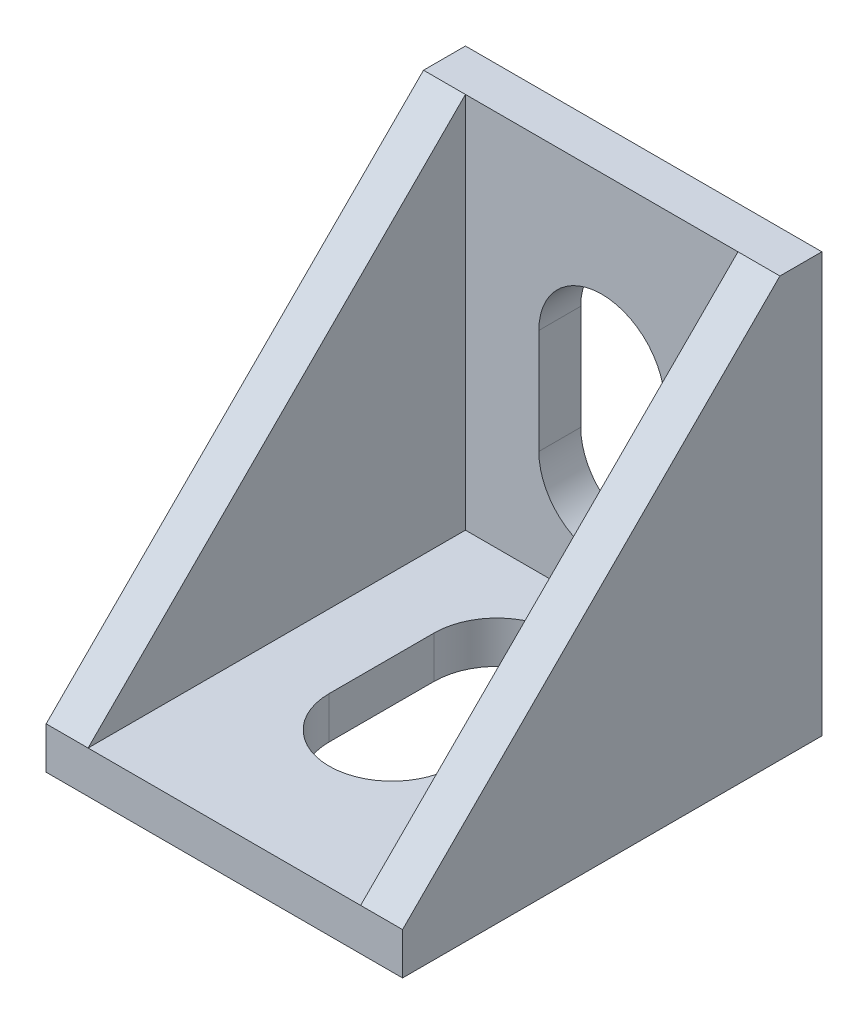
SolidWorks part; units mm, degrees
material "1060 Alloy"
ref_plane "Front Plane" through (0, 0, 0) normal (0, 0, 1) x (1, 0, 0)
ref_plane "Top Plane" through (0, 0, 0) normal (0, 1, 0) x (1, 0, 0)
ref_plane "Right Plane" through (0, 0, 0) normal (1, 0, 0) x (0, 0, -1)
sketch "Sketch1" plane through (0, 0, 0) normal (0, 0, 1) x (1, 0, 0)
  line L1 (-8.5, -10) -> (8.5, -10)
  line L2 (-8.5, -10) -> (-8.5, 10)
  line L3 (-8.5, 10) -> (8.5, 10)
  line L4 (8.5, -10) -> (8.5, 10)
  line L5 (-8.5, -10) -> (8.5, 10) construction
  line L6 (-8.5, 10) -> (8.5, -10) construction
  point P0 (0, 0)
  dimension "D1" = 17
  dimension "D2" = 20
extrude "Boss-Extrude1" add sketch "Sketch1" along normal blind 20
sketch "Sketch2" plane through (0, 10, 0) normal (0, 1, 0) x (1, 0, 0)
  line L0 (8.5, -20) -> (-8.5, -20) construction
  line L1 (-6.5, -20) -> (6.5, -20)
  line L2 (-6.5, -20) -> (-6.5, -2)
  line L3 (-6.5, -2) -> (6.5, -2)
  line L4 (6.5, -20) -> (6.5, -2)
  line L5 (-8.5, -20) -> (-8.5, 0) construction
  line L6 (8.5, -20) -> (8.5, 0) construction
  line L7 (8.5, 0) -> (-8.5, 0) construction
  dimension "D1" = 2
  dimension "D2" = 2
  dimension "D3" = 2
extrude "Cut-Extrude1" cut sketch "Sketch2" against normal blind 18
sketch "Sketch3" plane through (8.5, 0, 0) normal (1, 0, 0) x (0, 0, -1)
  line L0 (-2, 10) -> (-20, -8)
  line L1 (-20, 10) -> (0, 10) construction
  line L2 (-20, -10) -> (-20, 10) construction
  line L3 (-20, -8) -> (-20, 10)
  line L4 (-20, 10) -> (-2, 10)
  dimension "D1" = 18
  dimension "D2" = 18
extrude "Cut-Extrude2" cut sketch "Sketch3" against normal through all and the other way through all
sketch "Sketch4" plane through (0, -8, 0) normal (0, 1, 0) x (1, 0, 0)
  line L0 (0, -12) -> (0, -7) construction
  line L1 (-3, -12) -> (-3, -7)
  line L2 (3, -12) -> (3, -7)
  line L3 (0, -7) -> (0, -2) construction
  line L4 (6.5, -2) -> (-6.5, -2) construction
  arc A0 (-3, -12) -> (3, -12) centre (0, -12) ccw
  arc A1 (3, -7) -> (-3, -7) centre (0, -7) ccw
  point P3 (0, -9.5)
  dimension "D1" = 3
  dimension "D2" = 5
  dimension "D3" = 5
extrude "Cut-Extrude3" cut sketch "Sketch4" against normal up to next
sketch "Sketch5" plane through (0, 0, 2) normal (0, 0, 1) x (1, 0, 0)
  line L0 (0, -3) -> (0, 2) construction
  line L1 (-3, -3) -> (-3, 2)
  line L2 (3, -3) -> (3, 2)
  line L3 (6.5, -8) -> (-6.5, -8) construction
  arc A0 (-3, -3) -> (3, -3) centre (0, -3) ccw
  arc A1 (3, 2) -> (-3, 2) centre (0, 2) ccw
  point P3 (0, -0.5)
  dimension "D1" = 3
  dimension "D2" = 5
  dimension "D3" = 5
extrude "Cut-Extrude4" cut sketch "Sketch5" against normal up to next
sketch "Sketch6" plane through (0, -10, 0) normal (0, -1, 0) x (1, 0, 0)
  line L0 (-1, 18) -> (1, 18) construction
  line L1 (-1, 19) -> (1, 19)
  line L2 (-1, 17) -> (1, 17)
  line L3 (0, 18) -> (0, 20) construction
  line L4 (-8.5, 20) -> (8.5, 20) construction
  line L5 (-1, 2) -> (1, 2) construction
  line L6 (-1, 3) -> (1, 3)
  line L7 (-1, 1) -> (1, 1)
  line L8 (0, 18) -> (0, 2) construction
  line L9 (-8.5, 0) -> (8.5, 0) construction
  arc A0 (-1, 19) -> (-1, 17) centre (-1, 18) ccw
  arc A1 (1, 17) -> (1, 19) centre (1, 18) ccw
  arc A2 (-1, 3) -> (-1, 1) centre (-1, 2) ccw
  arc A3 (1, 1) -> (1, 3) centre (1, 2) ccw
  point P2 (0, 18)
  point P13 (0, 2)
  dimension "D1" = 1
  dimension "D2" = 2
  dimension "D3" = 2
  dimension "D4" = 2
extrude "Boss-Extrude2" add sketch "Sketch6" along normal blind 1
sketch "Sketch7" plane through (0, 0, 0) normal (0, 0, -1) x (-1, 0, 0)
  line L0 (1, -8) -> (-1, -8) construction
  line L1 (1, -9) -> (-1, -9)
  line L2 (1, -7) -> (-1, -7)
  line L3 (1, 8) -> (-1, 8) construction
  line L4 (1, 7) -> (-1, 7)
  line L5 (1, 9) -> (-1, 9)
  line L6 (0, -8) -> (0, -10) construction
  line L7 (8.5, -10) -> (-8.5, -10) construction
  line L8 (0, -8) -> (0, 8) construction
  line L9 (-8.5, 10) -> (8.5, 10) construction
  arc A0 (1, -9) -> (1, -7) centre (1, -8) ccw
  arc A1 (-1, -7) -> (-1, -9) centre (-1, -8) ccw
  arc A2 (1, 7) -> (1, 9) centre (1, 8) ccw
  arc A3 (-1, 9) -> (-1, 7) centre (-1, 8) ccw
  point P2 (0, -8)
  point P7 (0, 8)
  dimension "D3" = 1
  dimension "D4" = 2
  dimension "D1" = 2
  dimension "D2" = 2
extrude "Boss-Extrude3" add sketch "Sketch7" along normal blind 1
extrude "Cut-Extrude5" cut sketch "Sketch8" against normal through all
sketch "Sketch8" plane through (229.4439, 235, -55.2972) normal (0, 1, 0) x (-1, 0, 0)
  line L0 (230.4439, 73.2972) -> (228.4439, 73.2972) construction
  line L1 (230.4439, 72.1972) -> (228.4439, 72.1972)
  line L2 (230.4439, 74.3972) -> (228.4439, 74.3972)
  line L3 (230.4439, 57.2972) -> (228.4439, 57.2972) construction
  line L4 (230.4439, 56.1972) -> (228.4439, 56.1972)
  line L5 (230.4439, 58.3972) -> (228.4439, 58.3972)
  line L6 (183.4439, 73.2972) -> (181.4439, 73.2972) construction
  line L9 (183.4439, 72.1972) -> (181.4439, 72.1972)
  line L12 (183.4439, 74.3972) -> (181.4439, 74.3972)
  line L15 (183.4439, 57.2972) -> (181.4439, 57.2972) construction
  line L18 (183.4439, 56.1972) -> (181.4439, 56.1972)
  line L21 (183.4439, 58.3972) -> (181.4439, 58.3972)
  line L24 (136.4439, 73.2972) -> (134.4439, 73.2972) construction
  line L27 (136.4439, 72.1972) -> (134.4439, 72.1972)
  line L30 (136.4439, 74.3972) -> (134.4439, 74.3972)
  line L31 (136.4439, 57.2972) -> (134.4439, 57.2972) construction
  line L32 (136.4439, 56.1972) -> (134.4439, 56.1972)
  line L33 (136.4439, 58.3972) -> (134.4439, 58.3972)
  line L34 (89.4439, 73.2972) -> (87.4439, 73.2972) construction
  line L35 (89.4439, 72.1972) -> (87.4439, 72.1972)
  line L36 (89.4439, 74.3972) -> (87.4439, 74.3972)
  line L37 (89.4439, 57.2972) -> (87.4439, 57.2972) construction
  line L38 (89.4439, 56.1972) -> (87.4439, 56.1972)
  line L39 (89.4439, 58.3972) -> (87.4439, 58.3972)
  line L40 (42.4439, 73.2972) -> (40.4439, 73.2972) construction
  line L41 (42.4439, 72.1972) -> (40.4439, 72.1972)
  line L42 (42.4439, 74.3972) -> (40.4439, 74.3972)
  line L43 (42.4439, 57.2972) -> (40.4439, 57.2972) construction
  line L44 (42.4439, 56.1972) -> (40.4439, 56.1972)
  line L45 (42.4439, 58.3972) -> (40.4439, 58.3972)
  circle A0 centre (229.4439, 67.2972) radius 2.5
  arc A1 (230.4439, 72.1972) -> (230.4439, 74.3972) centre (230.4439, 73.2972) ccw
  arc A2 (228.4439, 74.3972) -> (228.4439, 72.1972) centre (228.4439, 73.2972) ccw
  arc A3 (230.4439, 56.1972) -> (230.4439, 58.3972) centre (230.4439, 57.2972) ccw
  arc A4 (228.4439, 58.3972) -> (228.4439, 56.1972) centre (228.4439, 57.2972) ccw
  circle A21 centre (182.4439, 67.2972) radius 2.5
  arc A22 (183.4439, 72.1972) -> (183.4439, 74.3972) centre (183.4439, 73.2972) ccw
  arc A23 (181.4439, 74.3972) -> (181.4439, 72.1972) centre (181.4439, 73.2972) ccw
  arc A24 (183.4439, 56.1972) -> (183.4439, 58.3972) centre (183.4439, 57.2972) ccw
  arc A25 (181.4439, 58.3972) -> (181.4439, 56.1972) centre (181.4439, 57.2972) ccw
  circle A26 centre (135.4439, 67.2972) radius 2.5
  arc A27 (136.4439, 72.1972) -> (136.4439, 74.3972) centre (136.4439, 73.2972) ccw
  arc A28 (134.4439, 74.3972) -> (134.4439, 72.1972) centre (134.4439, 73.2972) ccw
  arc A29 (136.4439, 56.1972) -> (136.4439, 58.3972) centre (136.4439, 57.2972) ccw
  arc A30 (134.4439, 58.3972) -> (134.4439, 56.1972) centre (134.4439, 57.2972) ccw
  circle A31 centre (88.4439, 67.2972) radius 2.5
  arc A32 (89.4439, 72.1972) -> (89.4439, 74.3972) centre (89.4439, 73.2972) ccw
  arc A33 (87.4439, 74.3972) -> (87.4439, 72.1972) centre (87.4439, 73.2972) ccw
  arc A34 (89.4439, 56.1972) -> (89.4439, 58.3972) centre (89.4439, 57.2972) ccw
  arc A35 (87.4439, 58.3972) -> (87.4439, 56.1972) centre (87.4439, 57.2972) ccw
  circle A36 centre (41.4439, 67.2972) radius 2.5
  arc A37 (42.4439, 72.1972) -> (42.4439, 74.3972) centre (42.4439, 73.2972) ccw
  arc A38 (40.4439, 74.3972) -> (40.4439, 72.1972) centre (40.4439, 73.2972) ccw
  arc A39 (42.4439, 56.1972) -> (42.4439, 58.3972) centre (42.4439, 57.2972) ccw
  arc A40 (40.4439, 58.3972) -> (40.4439, 56.1972) centre (40.4439, 57.2972) ccw
  point P6 (229.4439, 73.2972)
  point P11 (229.4439, 57.2972)
  point P26 (182.4439, 73.2972)
  point P31 (182.4439, 57.2972)
  point P42 (135.4439, 73.2972)
  point P47 (135.4439, 57.2972)
  point P58 (88.4439, 73.2972)
  point P63 (88.4439, 57.2972)
  point P74 (41.4439, 73.2972)
  point P79 (41.4439, 57.2972)
extrude "Cut-Extrude6" cut sketch "Sketch9" against normal through all
sketch "Sketch9" plane through (229.4439, -65.2972, -5) normal (0, 0, -1) x (-1, 0, 0)
  line L0 (230.4439, 73.2972) -> (228.4439, 73.2972) construction
  line L1 (230.4439, 72.1972) -> (228.4439, 72.1972)
  line L2 (230.4439, 74.3972) -> (228.4439, 74.3972)
  line L3 (230.4439, 57.2972) -> (228.4439, 57.2972) construction
  line L4 (230.4439, 56.1972) -> (228.4439, 56.1972)
  line L5 (230.4439, 58.3972) -> (228.4439, 58.3972)
  line L6 (183.4439, 73.2972) -> (181.4439, 73.2972) construction
  line L9 (183.4439, 72.1972) -> (181.4439, 72.1972)
  line L12 (183.4439, 74.3972) -> (181.4439, 74.3972)
  line L15 (183.4439, 57.2972) -> (181.4439, 57.2972) construction
  line L18 (183.4439, 56.1972) -> (181.4439, 56.1972)
  line L21 (183.4439, 58.3972) -> (181.4439, 58.3972)
  line L24 (136.4439, 73.2972) -> (134.4439, 73.2972) construction
  line L27 (136.4439, 72.1972) -> (134.4439, 72.1972)
  line L30 (136.4439, 74.3972) -> (134.4439, 74.3972)
  line L31 (136.4439, 57.2972) -> (134.4439, 57.2972) construction
  line L32 (136.4439, 56.1972) -> (134.4439, 56.1972)
  line L33 (136.4439, 58.3972) -> (134.4439, 58.3972)
  line L34 (89.4439, 73.2972) -> (87.4439, 73.2972) construction
  line L35 (89.4439, 72.1972) -> (87.4439, 72.1972)
  line L36 (89.4439, 74.3972) -> (87.4439, 74.3972)
  line L37 (89.4439, 57.2972) -> (87.4439, 57.2972) construction
  line L38 (89.4439, 56.1972) -> (87.4439, 56.1972)
  line L39 (89.4439, 58.3972) -> (87.4439, 58.3972)
  line L40 (42.4439, 73.2972) -> (40.4439, 73.2972) construction
  line L41 (42.4439, 72.1972) -> (40.4439, 72.1972)
  line L42 (42.4439, 74.3972) -> (40.4439, 74.3972)
  line L43 (42.4439, 57.2972) -> (40.4439, 57.2972) construction
  line L44 (42.4439, 56.1972) -> (40.4439, 56.1972)
  line L45 (42.4439, 58.3972) -> (40.4439, 58.3972)
  circle A0 centre (229.4439, 67.2972) radius 2.5
  arc A1 (230.4439, 72.1972) -> (230.4439, 74.3972) centre (230.4439, 73.2972) ccw
  arc A2 (228.4439, 74.3972) -> (228.4439, 72.1972) centre (228.4439, 73.2972) ccw
  arc A3 (230.4439, 56.1972) -> (230.4439, 58.3972) centre (230.4439, 57.2972) ccw
  arc A4 (228.4439, 58.3972) -> (228.4439, 56.1972) centre (228.4439, 57.2972) ccw
  circle A21 centre (182.4439, 67.2972) radius 2.5
  arc A22 (183.4439, 72.1972) -> (183.4439, 74.3972) centre (183.4439, 73.2972) ccw
  arc A23 (181.4439, 74.3972) -> (181.4439, 72.1972) centre (181.4439, 73.2972) ccw
  arc A24 (183.4439, 56.1972) -> (183.4439, 58.3972) centre (183.4439, 57.2972) ccw
  arc A25 (181.4439, 58.3972) -> (181.4439, 56.1972) centre (181.4439, 57.2972) ccw
  circle A26 centre (135.4439, 67.2972) radius 2.5
  arc A27 (136.4439, 72.1972) -> (136.4439, 74.3972) centre (136.4439, 73.2972) ccw
  arc A28 (134.4439, 74.3972) -> (134.4439, 72.1972) centre (134.4439, 73.2972) ccw
  arc A29 (136.4439, 56.1972) -> (136.4439, 58.3972) centre (136.4439, 57.2972) ccw
  arc A30 (134.4439, 58.3972) -> (134.4439, 56.1972) centre (134.4439, 57.2972) ccw
  circle A31 centre (88.4439, 67.2972) radius 2.5
  arc A32 (89.4439, 72.1972) -> (89.4439, 74.3972) centre (89.4439, 73.2972) ccw
  arc A33 (87.4439, 74.3972) -> (87.4439, 72.1972) centre (87.4439, 73.2972) ccw
  arc A34 (89.4439, 56.1972) -> (89.4439, 58.3972) centre (89.4439, 57.2972) ccw
  arc A35 (87.4439, 58.3972) -> (87.4439, 56.1972) centre (87.4439, 57.2972) ccw
  circle A36 centre (41.4439, 67.2972) radius 2.5
  arc A37 (42.4439, 72.1972) -> (42.4439, 74.3972) centre (42.4439, 73.2972) ccw
  arc A38 (40.4439, 74.3972) -> (40.4439, 72.1972) centre (40.4439, 73.2972) ccw
  arc A39 (42.4439, 56.1972) -> (42.4439, 58.3972) centre (42.4439, 57.2972) ccw
  arc A40 (40.4439, 58.3972) -> (40.4439, 56.1972) centre (40.4439, 57.2972) ccw
  point P6 (229.4439, 73.2972)
  point P11 (229.4439, 57.2972)
  point P26 (182.4439, 73.2972)
  point P31 (182.4439, 57.2972)
  point P42 (135.4439, 73.2972)
  point P47 (135.4439, 57.2972)
  point P58 (88.4439, 73.2972)
  point P63 (88.4439, 57.2972)
  point P74 (41.4439, 73.2972)
  point P79 (41.4439, 57.2972)
